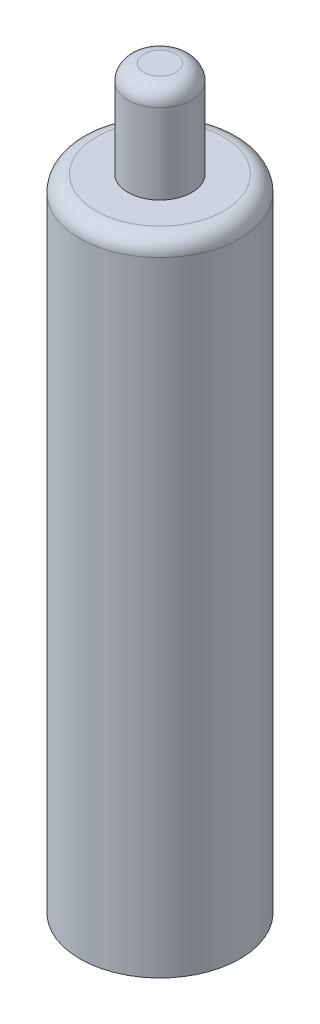
SolidWorks part; units mm, degrees
ref_plane "Front Plane" through (0, 0, 0) normal (0, 0, 1) x (1, 0, 0)
ref_plane "Top Plane" through (0, 0, 0) normal (0, 1, 0) x (1, 0, 0)
ref_plane "Right Plane" through (0, 0, 0) normal (1, 0, 0) x (0, 0, -1)
sketch "Sketch1" plane through (0, 0, 0) normal (0, 1, 0) x (1, 0, 0)
  circle A0 centre (0, 0) radius 2.5
  dimension "D1" = 5
extrude "Boss-Extrude1" add sketch "Sketch1" along normal blind 20
sketch "Sketch2" plane through (0, 20, 0) normal (0, 1, 0) x (1, 0, 0)
  circle A0 centre (0, 0) radius 1
  dimension "D1" = 2
extrude "Boss-Extrude2" add sketch "Sketch2" along normal blind 3
fillet "Fillet1" radius 0.5 2 edges at (0, 20, 2.5) (0, 23, 1)
